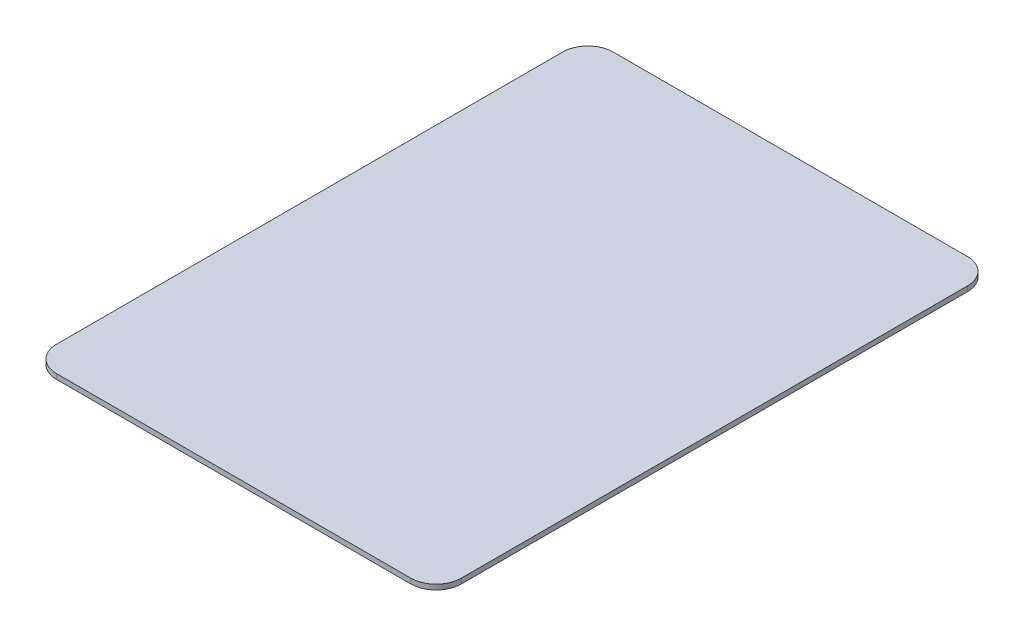
SolidWorks part; units mm, degrees
ref_plane "Front Plane" through (0, 0, 0) normal (0, 0, 1) x (1, 0, 0)
ref_plane "Top Plane" through (0, 0, 0) normal (0, 1, 0) x (1, 0, 0)
ref_plane "Right Plane" through (0, 0, 0) normal (1, 0, 0) x (0, 0, -1)
sketch "Sketch1" plane through (0, 0, 0) normal (0, 1, 0) x (1, 0, 0)
  line L1 (-254, 349.25) -> (254, 349.25)
  line L2 (-254, 349.25) -> (-254, -349.25)
  line L3 (-254, -349.25) -> (254, -349.25)
  line L4 (254, 349.25) -> (254, -349.25)
  line L5 (-254, 349.25) -> (254, -349.25) construction
  line L6 (-254, -349.25) -> (254, 349.25) construction
  point P0 (0, 0)
  dimension "D1" = 508
  dimension "D2" = 698.5
extrude "Boss-Extrude1" add sketch "Sketch1" along normal blind 6.35
fillet "Fillet1" radius 31.75 4 edges at (-254, 3.175, -349.25) (-254, 3.175, 349.25) (254, 3.175, 349.25) (254, 3.175, -349.25)
